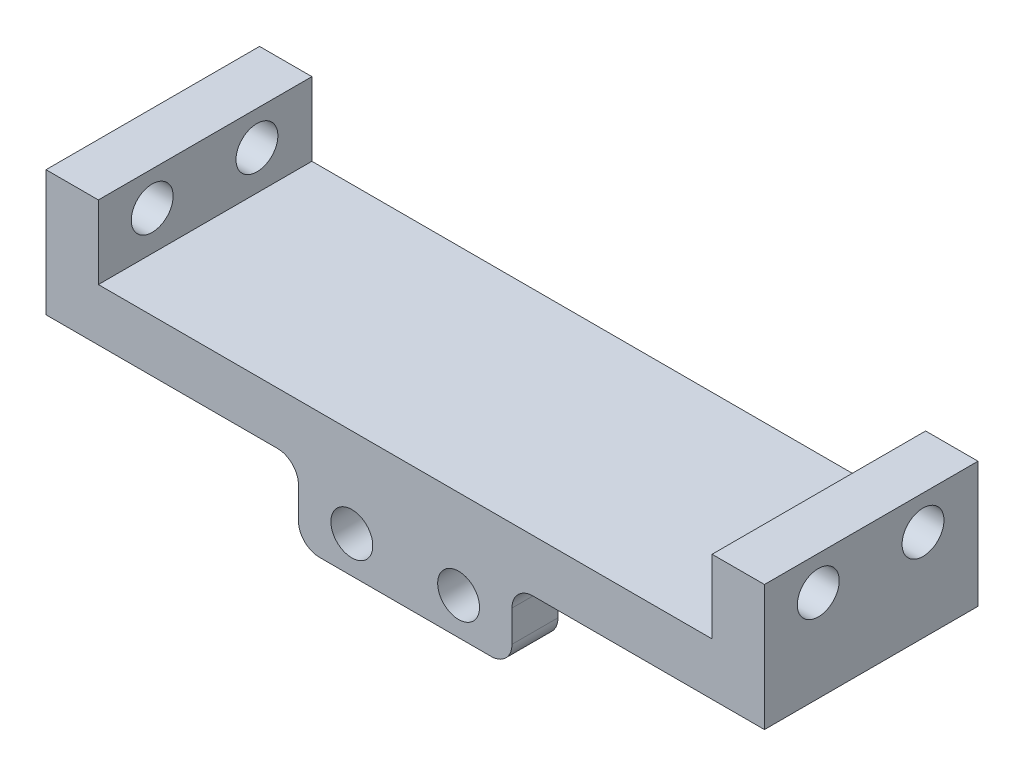
SolidWorks part; units mm, degrees
ref_plane "Front" through (0, 0, 0) normal (0, 0, 1) x (1, 0, 0)
ref_plane "Top" through (0, 0, 0) normal (0, 1, 0) x (1, 0, 0)
ref_plane "Right" through (0, 0, 0) normal (1, 0, 0) x (0, 0, -1)
sketch "Sketch1" plane through (0, 0, 0) normal (0, 1, 0) x (1, 0, 0)
  line L1 (0, 0) -> (68.6, 0)
  line L2 (0, 0) -> (0, 20.3898)
  line L3 (0, 20.3898) -> (68.6, 20.3898)
  line L4 (68.6, 0) -> (68.6, 20.3898)
  dimension "D1" = 68.6
  dimension "D2" = 20.3898
extrude "bracketBase" add sketch "Sketch1" along normal blind 5
sketch "Sketch2" plane through (0, 0, 0) normal (-1, 0, 0) x (0, 0, 1)
  line L0 (0, 5) -> (0, 0) construction
  line L1 (-20.3898, 0) -> (0, 0)
  line L2 (-20.3898, 0) -> (-20.3898, 12)
  line L3 (-20.3898, 12) -> (0, 12)
  line L4 (0, 0) -> (0, 12)
  line L5 (-20.3898, 5) -> (0, 5) construction
  dimension "D1" = 7
extrude "legMountingTab" add sketch "Sketch2" against normal blind 5
sketch "Sketch3" plane through (5, 0, 0) normal (1, 0, 0) x (0, 0, -1)
  line L0 (20.3898, 12) -> (20.3898, 5) construction
  line L1 (0, 12) -> (20.3898, 12) construction
  circle A0 centre (15.1398, 8.75) radius 2
  circle A1 centre (5.1398, 8.75) radius 2
  dimension "D1" = 4
  dimension "D2" = 5.25
  dimension "D3" = 3.25
  dimension "D4" = 10
extrude "legMountingHoles" cut sketch "Sketch3" against normal blind 5
ref_plane "Plane1" through (34.3, 0, 0) normal (-1, 0, 0) x (0, 0, 1)
mirror "legMountingHoles2" about plane through (34.3, 0, 0) normal (-1, 0, 0) of "legMountingHoles", "legMountingTab"
sketch "Sketch4" plane through (0, 0, 0) normal (0, 0, 1) x (1, 0, 0)
  line L0 (0, 0) -> (68.6, 0) construction
  line L1 (44.4949, 0) -> (24.1051, 0)
  line L2 (44.4949, 0) -> (44.4949, -7)
  line L3 (44.4949, -7) -> (24.1051, -7)
  line L4 (24.1051, 0) -> (24.1051, -7)
  point P4 (34.3, 0)
  point P7 (34.3, 0)
  dimension "D1" = 7
  dimension "D2" = 20.3898
extrude "arduinoMountingTab" add sketch "Sketch4" against normal blind 4.3898
sketch "Sketch5" plane through (0, 0, 0) normal (0, 0, 1) x (1, 0, 0)
  line L2 (34.3, -7) -> (34.3, 5) construction
  line L3 (24.1051, -7) -> (44.4949, -7) construction
  line L4 (5, 5) -> (63.6, 5) construction
  line L5 (44.4949, -3.5) -> (34.3, -3.5) construction
  line L8 (44.4949, -7) -> (44.4949, 0) construction
  circle A0 centre (39.3974, -3.5) radius 2
  circle A1 centre (29.2026, -3.5) radius 2
  dimension "D1" = 4
extrude "arduinoMountingHoles" cut sketch "Sketch5" against normal blind 5
fillet "Fillet1" radius 2 4 edges at (24.1051, -7, -2.1949) (44.4949, -7, -2.1949) (44.4949, 0, -2.1949) (24.1051, 0, -2.1949)
